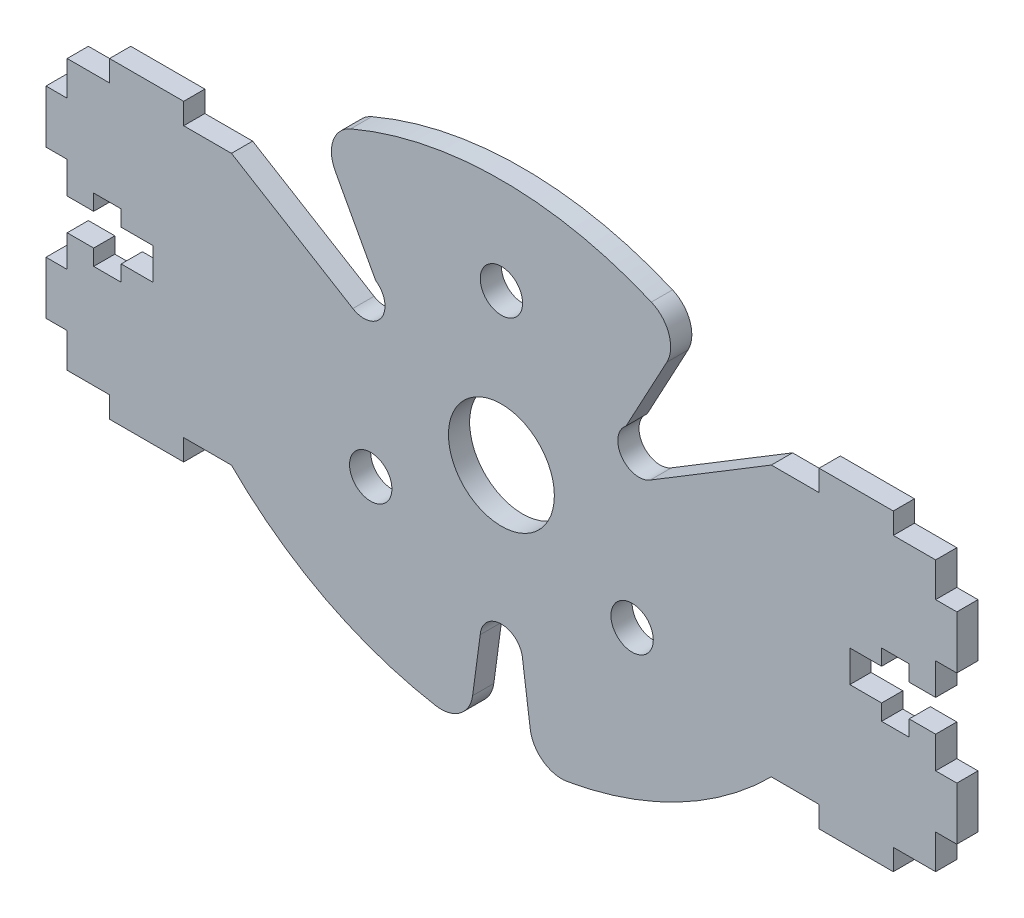
SolidWorks part; units mm, degrees
ref_plane "前视基准面" through (0, 0, 0) normal (0, 0, 1) x (1, 0, 0)
ref_plane "上视基准面" through (0, 0, 0) normal (0, 1, 0) x (1, 0, 0)
ref_plane "右视基准面" through (0, 0, 0) normal (1, 0, 0) x (0, 0, -1)
sketch "草图1" plane through (0, 0, 0) normal (0, 0, 1) x (1, 0, 0)
  line L19 (-37, -12.75) -> (-41, -12.75)
  line L145 (-37, -14.75) -> (-37, -12.75)
  line L152 (-30, -12.75) -> (-30, -14.75)
  line L205 (-30, 12.75) -> (-25.489, 12.75)
  line L238 (-30, -12.75) -> (-25.489, -12.75)
  line L269 (25.489, -12.75) -> (30, -12.75)
  line L270 (25.489, 12.75) -> (30, 12.75)
  line L271 (-37, -14.75) -> (-30, -14.75)
  line L275 (37, -14.75) -> (30, -14.75)
  line L286 (30, -12.75) -> (30, -14.75)
  line L287 (37, -14.75) -> (37, -12.75)
  line L288 (37, -12.75) -> (41, -12.75)
  line L291 (37, 12.75) -> (41, 12.75)
  line L292 (37, 14.75) -> (37, 12.75)
  line L293 (30, 12.75) -> (30, 14.75)
  line L304 (37, 14.75) -> (30, 14.75)
  line L310 (-37, 14.75) -> (-30, 14.75)
  line L325 (-30, 12.75) -> (-30, 14.75)
  line L326 (-37, 14.75) -> (-37, 12.75)
  line L327 (-37, 12.75) -> (-41, 12.75)
  line L337 (-41, 1.5) -> (-41, 4.5)
  line L338 (-41, 4.5) -> (-43, 4.5)
  line L339 (-43, 4.5) -> (-43, 9.5)
  line L340 (-43, 9.5) -> (-41, 9.5)
  line L341 (-41, 9.5) -> (-41, 12.75)
  line L342 (-41, -9.5) -> (-41, -12.75)
  line L343 (-43, -9.5) -> (-41, -9.5)
  line L344 (-43, -4.5) -> (-43, -9.5)
  line L345 (-41, -4.5) -> (-43, -4.5)
  line L346 (-41, -1.5) -> (-41, -4.5)
  line L358 (41, -1.5) -> (41, -4.5)
  line L359 (41, -4.5) -> (43, -4.5)
  line L360 (43, -4.5) -> (43, -9.5)
  line L361 (43, -9.5) -> (41, -9.5)
  line L362 (41, -9.5) -> (41, -12.75)
  line L363 (41, 9.5) -> (41, 12.75)
  line L364 (43, 9.5) -> (41, 9.5)
  line L365 (43, 4.5) -> (43, 9.5)
  line L366 (41, 4.5) -> (43, 4.5)
  line L367 (41, 1.5) -> (41, 4.5)
  line L371 (0, 0) -> (0, -33.9425) construction
  line L372 (-38.5, -1.5) -> (-38.5, -3)
  line L373 (-32.9, 1.5) -> (-32.9, -1.5)
  line L374 (-38.5, 1.5) -> (-38.5, 3)
  line L375 (-41, 1.5) -> (-38.5, 1.5)
  line L376 (-38.5, -3) -> (-35.9, -3)
  line L377 (-35.9, -3) -> (-35.9, -1.5)
  line L378 (-35.9, -1.5) -> (-32.9, -1.5)
  line L379 (-35.9, 1.5) -> (-32.9, 1.5)
  line L380 (-35.9, 3) -> (-35.9, 1.5)
  line L381 (-38.5, 3) -> (-35.9, 3)
  line L382 (-38.5, -1.5) -> (-41, -1.5)
  line L383 (0, 0) -> (27.1372, 15.6677) construction
  line L384 (38.5, -1.5) -> (41, -1.5)
  line L385 (41, 1.5) -> (38.5, 1.5)
  line L386 (38.5, 3) -> (35.9, 3)
  line L387 (35.9, 3) -> (35.9, 1.5)
  line L388 (35.9, 1.5) -> (32.9, 1.5)
  line L389 (35.9, -1.5) -> (32.9, -1.5)
  line L390 (35.9, -3) -> (35.9, -1.5)
  line L391 (38.5, -3) -> (35.9, -3)
  line L392 (38.5, 1.5) -> (38.5, 3)
  line L393 (32.9, 1.5) -> (32.9, -1.5)
  line L394 (38.5, -1.5) -> (38.5, -3)
  line L395 (0, 0) -> (-36.5927, 21.1268) construction
  line L396 (0, 0) -> (4.3337, -32.2123) construction
  line L397 (0, 0) -> (-5.0073, -37.2194) construction
  line L398 (0, 0) -> (-25.2087, 19.457) construction
  line L399 (0, 0) -> (25.3843, 19.5925) construction
  line L400 (25.489, 12.75) -> (14.0571, 5.8083)
  line L401 (11.7684, 9.0833) -> (15.6213, 16.2277)
  line L402 (-11.8771, 9.1615) -> (-15.6893, 16.1909)
  line L403 (-25.489, 12.75) -> (-14.0285, 5.7905)
  line L404 (2.7195, -20.2139) -> (2, -14.8661)
  line L405 (-2.7195, -20.2139) -> (-2, -14.8661)
  circle A13 centre (0, 0) radius 15 construction
  circle A14 centre (0, 0) radius 14.25 construction
  circle A21 centre (0, 14.25) radius 2
  circle A22 centre (12.3409, -7.125) radius 2
  circle A23 centre (-12.3409, -7.125) radius 2
  circle A24 centre (0, 0) radius 5
  arc A25 (25.489, -12.75) -> (-25.489, -12.75) centre (0, 12.739) cw construction
  arc A27 (14.0571, 5.8083) -> (11.7684, 9.0833) centre (12.9904, 7.5) cw
  arc A28 (-14.0285, 5.7905) -> (-11.8771, 9.1615) centre (-12.9904, 7.5) ccw
  circle A29 centre (12.9904, 7.5) radius 2 construction
  circle A30 centre (0, -15) radius 2 construction
  circle A31 centre (-12.9904, 7.5) radius 2 construction
  arc A32 (2, -14.8661) -> (-2, -14.8661) centre (0, -15.0022) ccw
  arc A33 (25.489, -12.75) -> (6.2095, -22.769) centre (0, 12.739) cw
  arc A34 (-6.2095, -22.769) -> (-25.489, -12.75) centre (0, 12.739) cw
  arc A35 (14.1592, 20.4106) -> (-14.2371, 20.3772) centre (0, -12.739) ccw
  arc A36 (-6.2095, -22.769) -> (-2.7195, -20.2139) centre (-5.6927, -19.8139) ccw
  arc A37 (6.2095, -22.769) -> (2.7195, -20.2139) centre (5.6927, -19.8139) cw
  arc A38 (-15.6893, 16.1909) -> (-14.2371, 20.3772) centre (-13.0522, 17.6211) cw
  arc A39 (14.1592, 20.4106) -> (15.6213, 16.2277) centre (12.9808, 17.6517) cw
  point P81 (-3.1175, -23.1728)
  point P88 (3.1175, -23.1728)
  dimension "D1" = 3
  dimension "D3" = 3
  dimension "D2" = 120
  dimension "D5" = 4
  dimension "D6" = 4
  dimension "D7" = 4
  dimension "D8" = 3
  dimension "D4" = 120
extrude "凸台-拉伸2" add sketch "草图1" along normal blind 2
sketch "草图2" plane through (41, 0, 0) normal (1, 0, 0) x (0, 0, -1)
  line L0 (-1, 1.5) -> (-1, -1.5) construction
  line L1 (-2, 1.5) -> (0, 1.5) construction
  line L2 (-2, -1.5) -> (0, -1.5) construction
  circle A0 centre (-1, 0) radius 1.5 construction
sketch "草图3" plane through (-41, 0, 0) normal (-1, 0, 0) x (0, 0, 1)
  line L0 (1, 1.5) -> (1, -1.5) construction
  line L1 (2, 1.5) -> (0, 1.5) construction
  line L2 (2, -1.5) -> (0, -1.5) construction
  circle A0 centre (1, 0) radius 1.5 construction
